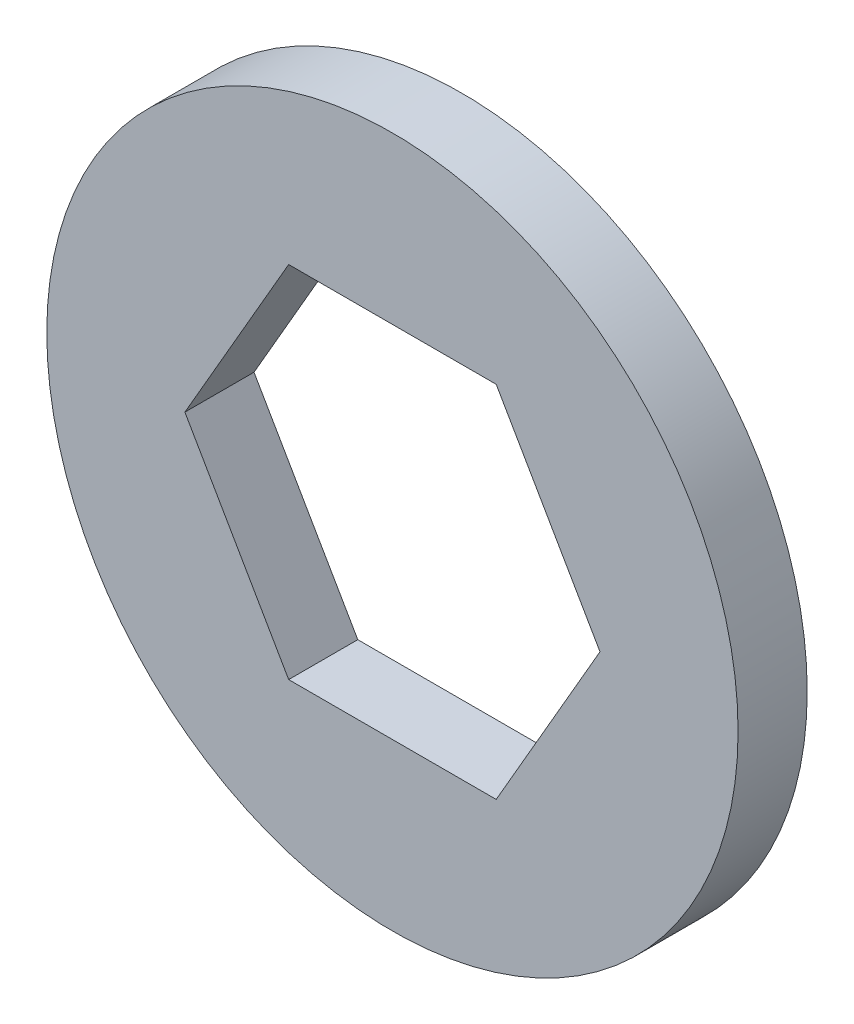
SolidWorks part; units mm, degrees
ref_plane "Front Plane" through (0, 0, 0) normal (0, 0, 1) x (1, 0, 0)
ref_plane "Top Plane" through (0, 0, 0) normal (0, 1, 0) x (1, 0, 0)
ref_plane "Right Plane" through (0, 0, 0) normal (1, 0, 0) x (0, 0, -1)
sketch "Sketch1" plane through (0, 0, 0) normal (0, 0, 1) x (1, 0, 0)
  line L1 (3.8128, -6.604) -> (7.6256, 0)
  line L2 (7.6256, 0) -> (3.8128, 6.604)
  line L3 (3.8128, 6.604) -> (-3.8128, 6.604)
  line L4 (-3.8128, 6.604) -> (-7.6256, 0)
  line L5 (-7.6256, 0) -> (-3.8128, -6.604)
  line L6 (-3.8128, -6.604) -> (3.8128, -6.604)
  circle A0 centre (0, 0) radius 6.604 construction
  circle A1 centre (0, 0) radius 12.7
  dimension "D2" = 25.4
  dimension "D1" = 13.208
extrude "Boss-Extrude1" add sketch "Sketch1" along normal blind 2.54
